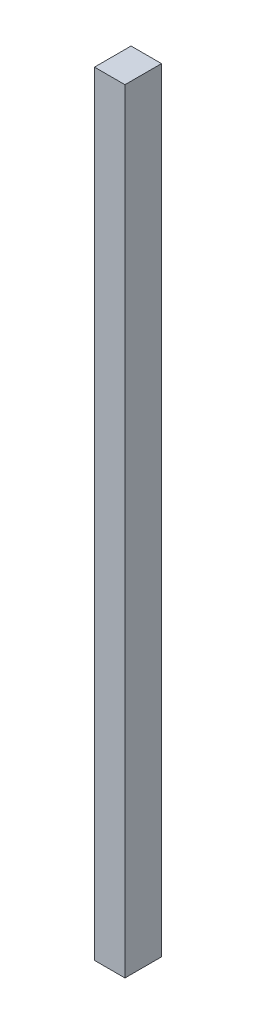
SolidWorks part; units mm, degrees
ref_plane "Front Plane" through (0, 0, 0) normal (0, 0, 1) x (1, 0, 0)
ref_plane "Top Plane" through (0, 0, 0) normal (0, 1, 0) x (1, 0, 0)
ref_plane "Right Plane" through (0, 0, 0) normal (1, 0, 0) x (0, 0, -1)
sketch "Sketch1" plane through (0, 0, 0) normal (0, 1, 0) x (1, 0, 0)
  line L1 (-2.5, -3) -> (2.5, -3)
  line L2 (-2.5, -3) -> (-2.5, 3)
  line L3 (-2.5, 3) -> (2.5, 3)
  line L4 (2.5, -3) -> (2.5, 3)
  line L5 (-2.5, -3) -> (2.5, 3) construction
  line L6 (-2.5, 3) -> (2.5, -3) construction
  point P0 (0, 0)
  dimension "D1" = 5
  dimension "D2" = 6
extrude "Boss-Extrude1" add sketch "Sketch1" along normal blind 127
